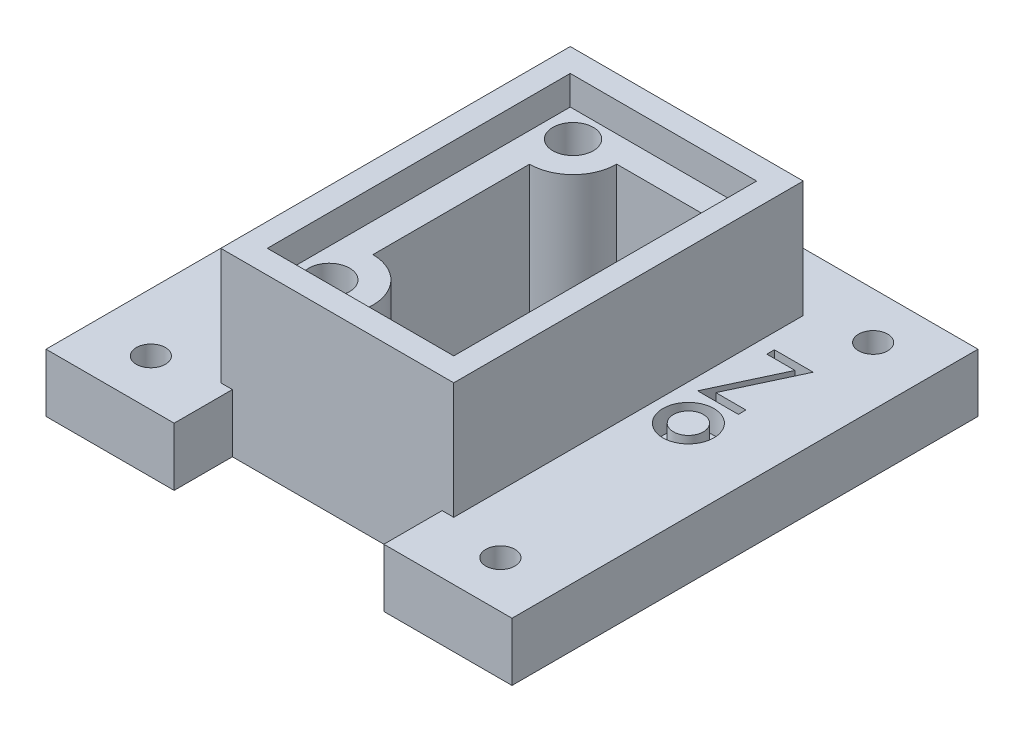
SolidWorks part; units mm, degrees
ref_plane "Front" through (0, 0, 0) normal (0, 0, 1) x (1, 0, 0)
ref_plane "Top" through (0, 0, 0) normal (0, 1, 0) x (1, 0, 0)
ref_plane "Right" through (0, 0, 0) normal (1, 0, 0) x (0, 0, -1)
sketch "Sketch1" plane through (0, 0, 0) normal (0, 1, 0) x (1, 0, 0)
  line L0 (-8.0987, 18.7927) -> (-8.0987, -52.9321) construction
  line L1 (-28.0987, 18.7927) -> (11.9013, 18.7927)
  line L2 (-28.0987, 18.7927) -> (-28.0987, -21.2073)
  line L3 (-28.0987, -21.2073) -> (-17.0987, -21.2073)
  line L4 (11.9013, 18.7927) -> (11.9013, -21.2073)
  line L5 (-28.0987, -1.2073) -> (21.4934, -1.2073) construction
  line L6 (-39.8723, -16.2073) -> (21.4934, -16.2073) construction
  line L7 (-17.0987, -21.2073) -> (-17.0987, -16.2073)
  line L8 (-17.0987, -16.2073) -> (0.9013, -16.2073)
  line L9 (0.9013, -21.2073) -> (0.9013, -16.2073)
  line L10 (0.9013, -21.2073) -> (11.9013, -21.2073)
  point P14 (-8.0987, -16.2073)
  dimension "D1" = 40
  dimension "D2" = 40
  dimension "D3" = 5
  dimension "D4" = 9
extrude "Boss-Extrude1" add sketch "Sketch1" along normal blind 5
sketch "Sketch2" plane through (0, 5, 0) normal (0, 1, 0) x (1, 0, 0)
  line L0 (-8.0987, 18.7927) -> (-8.0987, -31.7546) construction
  line L1 (11.9013, 18.7927) -> (-28.0987, 18.7927) construction
  line L2 (-28.0987, -1.2073) -> (20.4926, -1.2073) construction
  line L3 (-28.0987, 18.7927) -> (-28.0987, -21.2073) construction
  line L5 (-18.0987, 13.7927) -> (1.9013, 13.7927)
  line L6 (-18.0987, 13.7927) -> (-18.0987, -16.2073)
  line L7 (-18.0987, -16.2073) -> (1.9013, -16.2073)
  line L8 (1.9013, 13.7927) -> (1.9013, -16.2073)
  dimension "D1" = 20
  dimension "D2" = 30
  dimension "D3" = 10
  dimension "D4" = 15
extrude "Boss-Extrude2" add sketch "Sketch2" along normal blind 10
sketch "Sketch3" plane through (0, 15, 0) normal (0, 1, 0) x (1, 0, 0)
  line L0 (-18.0987, -1.2073) -> (10.7494, -1.2073) construction
  line L1 (-18.0987, 13.7927) -> (-18.0987, -16.2073) construction
  line L2 (-8.0987, 13.7927) -> (-8.0987, -18.2398) construction
  line L3 (1.9013, 13.7927) -> (-18.0987, 13.7927) construction
  line L6 (-16.0987, 11.7927) -> (-0.0987, 11.7927)
  line L7 (-16.0987, 11.7927) -> (-16.0987, -14.2073)
  line L8 (-16.0987, -14.2073) -> (-0.0987, -14.2073)
  line L9 (-0.0987, 11.7927) -> (-0.0987, -14.2073)
  dimension "D1" = 16
  dimension "D2" = 26
  dimension "D3" = 13
  dimension "D4" = 8
extrude "Cut-Extrude1" cut sketch "Sketch3" against normal blind 2.5
sketch "Sketch4" plane through (0, 12.5, 0) normal (0, 1, 0) x (1, 0, 0)
  line L0 (-16.0987, -14.2073) -> (-0.0987, -14.2073) construction
  line L1 (-16.0987, 11.7927) -> (-16.0987, -14.2073) construction
  line L2 (-9.8577, 9.5427) -> (-2.5987, 9.5427)
  line L3 (-0.0987, -14.2073) -> (-0.0987, 11.7927) construction
  line L4 (-13.5987, 9.5337) -> (-13.5987, -21.7863) construction
  line L5 (-4.295, -11.7073) -> (-31.4682, -11.7073) construction
  line L9 (-2.5987, 9.5427) -> (-2.5987, -11.7073)
  line L10 (-2.5987, -11.7073) -> (-9.8622, -11.7073)
  line L11 (-13.5987, -7.6509) -> (-13.5987, 5.7927)
  circle A1 centre (-13.5987, -11.4) radius 3.7492 construction
  circle A2 centre (-13.5987, 9.5337) radius 1.7411
  circle A3 centre (-13.5987, -11.4) radius 1.7492
  arc A4 (-13.5987, 5.7927) -> (-9.8577, 9.5427) centre (-13.5987, 9.5337) ccw
  arc A5 (-9.8622, -11.7073) -> (-13.5987, -7.6509) centre (-13.5987, -11.4) ccw
  circle A7 centre (-13.5987, 9.5337) radius 3.7411 construction
  point P1 (1.9201, 13.7901)
  point P2 (-13.0799, -11.2099)
  point P6 (1.9201, -11.2099)
  point P10 (-13.0799, 13.7901)
  point P13 (-11.0799, 11.7901)
  point P16 (-11.0799, -9.2099)
  point P17 (-7.5799, 11.5401)
  point P19 (-7.5799, -8.9599)
  dimension "D3" = 3.4821
  dimension "D6" = 3.4983
  dimension "D1" = 2.5
  dimension "D2" = 2.5
  dimension "D4" = 2.5
  dimension "D9" = 2
extrude "Cut-Extrude2" cut sketch "Sketch4" against normal up to surface (12.5 mm away) up to face at (-8.0987, 0, 9.9573)
sketch "Sketch5" plane through (0, 0, 0) normal (0, -1, 0) x (1, 0, 0)
  line L1 (-11.0131, 9.7636) -> (-10.8887, 12.821)
  line L2 (-10.8887, 12.821) -> (-13.4743, 14.4575)
  line L3 (-13.4743, 14.4575) -> (-16.1843, 13.0365)
  line L4 (-16.1843, 13.0365) -> (-16.3087, 9.979)
  line L5 (-16.3087, 9.979) -> (-13.7231, 8.3426)
  line L6 (-13.7231, 8.3426) -> (-11.0131, 9.7636)
  line L7 (-10.5398, -9.6146) -> (-11.9993, -6.9251)
  line L8 (-11.9993, -6.9251) -> (-15.0581, -6.8442)
  line L9 (-15.0581, -6.8442) -> (-16.6576, -9.4529)
  line L10 (-16.6576, -9.4529) -> (-15.1982, -12.1424)
  line L11 (-15.1982, -12.1424) -> (-12.1393, -12.2232)
  line L12 (-12.1393, -12.2232) -> (-10.5398, -9.6146)
  circle A0 centre (-13.5987, 11.4) radius 2.65 construction
  circle A1 centre (-13.5987, -9.5337) radius 2.65 construction
  dimension "D1" = 5.3
  dimension "D2" = 5.3
extrude "Cut-Extrude3" cut sketch "Sketch5" against normal blind 2.5
sketch "Sketch10" plane through (0, 5, 0) normal (0, 1, 0) x (1, 0, 0)
  line L2 (1.9013, 13.7927) -> (-18.0987, 13.7927) construction
  line L3 (-17.9386, 3.2714) -> (-23.2666, 3.2714) construction
  line L4 (-17.9386, -4.5372) -> (-17.9386, 7.2326) construction
  line L5 (-23.2666, -4.5372) -> (-23.2666, 7.5813) construction
  circle A0 centre (4.9717, 0.864) radius 2.1872
  circle A2 centre (4.9717, 0.864) radius 1.286
  text T0 "X" font "Century Gothic" height in points 18
  text T1 "k" font "SWAstro" height 6.35
  text T2 "Y"
  text T3 "l" font "SWAstro" height 6.35
  text T4 "Z"
extrude "Cut-Extrude7" cut sketch "Sketch10" against normal blind 2
sketch "Sketch11" plane through (0, 5, 0) normal (0, 1, 0) x (1, 0, 0)
  line L0 (-8.0987, 18.7927) -> (-8.0987, -21.2073) construction
  line L1 (11.9013, 18.7927) -> (-28.0987, 18.7927) construction
  line L3 (-28.0987, -1.2073) -> (11.9013, -1.2073) construction
  line L4 (-28.0987, 18.7927) -> (-28.0987, -21.2073) construction
  line L5 (11.9013, -21.2073) -> (11.9013, 18.7927) construction
  circle A0 centre (-23.0987, 14.7927) radius 1.25
  circle A1 centre (6.9013, 14.7927) radius 1.25
  circle A2 centre (6.9013, -17.2073) radius 1.25
  circle A3 centre (-23.0987, -17.2073) radius 1.25
  dimension "D1" = 2.5
  dimension "D2" = 4
  dimension "D3" = 5
extrude "Cut-Extrude8" cut sketch "Sketch11" against normal up to surface (5 mm away) up to face at (-13.5987, 0, -9.5337)
